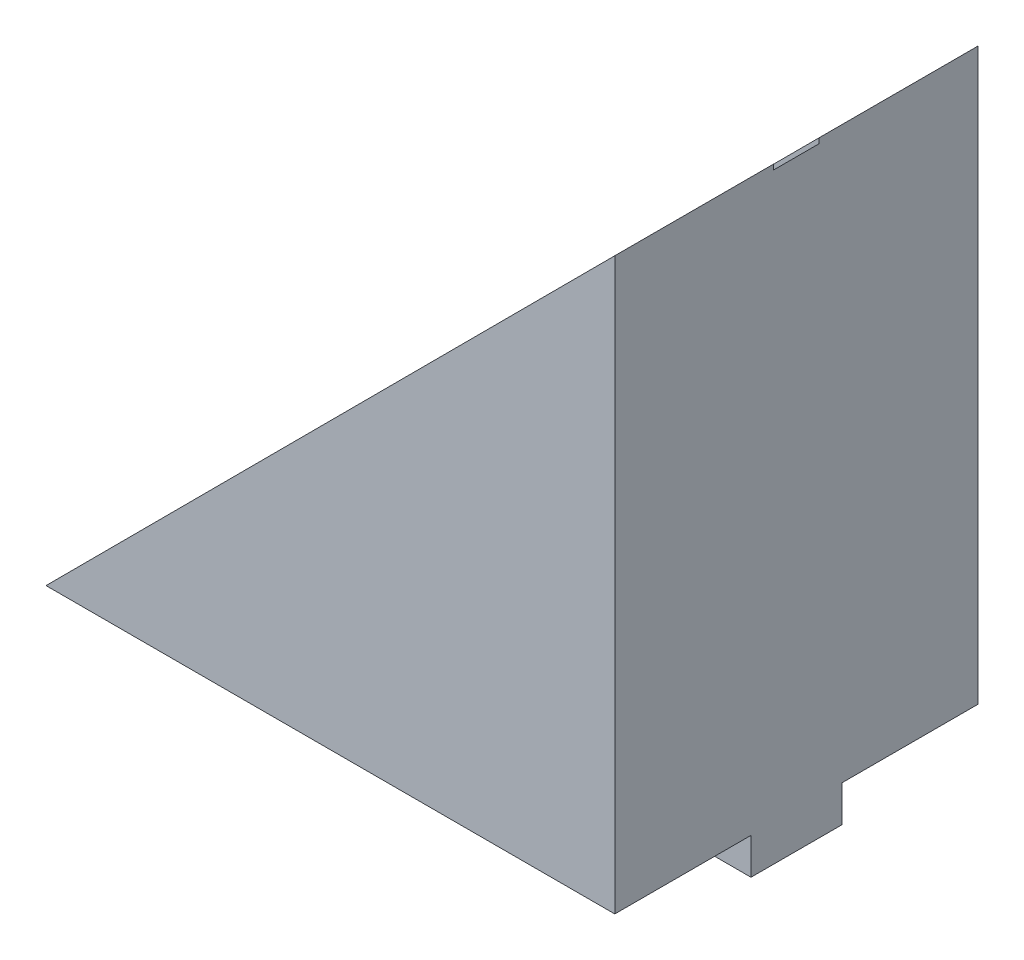
SolidWorks part; units mm, degrees
ref_plane "Front Plane" through (0, 0, 0) normal (0, 0, 1) x (1, 0, 0)
ref_plane "Top Plane" through (0, 0, 0) normal (0, 1, 0) x (1, 0, 0)
ref_plane "Right Plane" through (0, 0, 0) normal (1, 0, 0) x (0, 0, -1)
sketch "Sketch1" plane through (0, 0, 0) normal (0, 0, 1) x (1, 0, 0)
  line L0 (0, 0) -> (16.7126, 0)
  line L1 (39.7753, 0) -> (39.7753, 39.8649)
  line L2 (39.7753, 39.8649) -> (0, 0)
  line L3 (23.0626, 0) -> (39.7753, 0)
  line L7 (16.7126, 0) -> (23.0626, 0)
  point P11 (19.8876, -3.8693)
extrude "Boss-Extrude1" add sketch "Sketch1" along normal blind 25.4
sketch "Sketch3" plane through (0, 0, 0) normal (0, -1, 0) x (1, 0, 0)
  line L0 (0, 12.7) -> (39.7753, 12.7) construction
  line L3 (0, 25.4) -> (0, 0) construction
  line L4 (39.7753, 25.4) -> (39.7753, 0) construction
  line L5 (0, 9.525) -> (0, 15.875)
  line L6 (0, 15.875) -> (39.7753, 15.875)
  line L7 (39.7753, 15.875) -> (39.7753, 9.525)
  line L8 (39.7753, 9.525) -> (0, 9.525)
  dimension "D1" = 3.175
extrude "Boss-Extrude2" add sketch "Sketch3" along normal blind 2.54
sketch "Sketch4" plane through (0, 0, 0) normal (-0.7079, 0.7063, 0) x (0, 0, 1)
  line L1 (25.4, 56.3141) -> (0, 56.3141) construction
  line L2 (15.875, 0) -> (9.525, 0) construction
  line L3 (11.1125, 56.3141) -> (11.1125, 0)
  line L4 (14.2875, 56.3141) -> (14.2875, 0)
  line L5 (11.1125, 56.3141) -> (14.2875, 56.3141)
  line L6 (11.1125, 0) -> (14.2875, 0)
extrude "Cut-Extrude1" cut sketch "Sketch4" against normal blind 0.254
